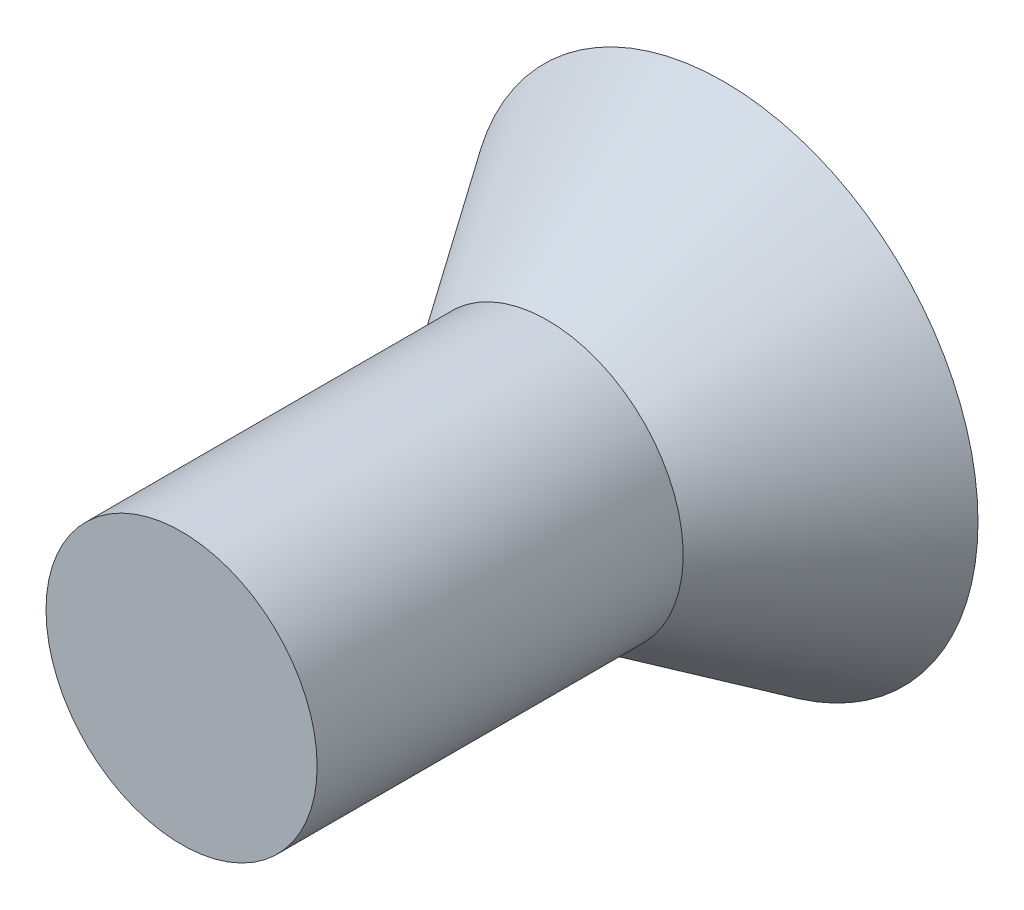
SolidWorks part; units mm, degrees
ref_plane "前视基准面" through (0, 0, 0) normal (0, 0, 1) x (1, 0, 0)
ref_plane "上视基准面" through (0, 0, 0) normal (0, 1, 0) x (1, 0, 0)
ref_plane "右视基准面" through (0, 0, 0) normal (1, 0, 0) x (0, 0, -1)
sketch "草图1" plane through (0, 0, 0) normal (0, 0, 1) x (1, 0, 0)
  circle A0 centre (0, 0) radius 2
extrude "凸台-拉伸1" add sketch "草图1" along normal blind 8
sketch "草图2" plane through (0, 0, 0) normal (0, 1, 0) x (1, 0, 0)
  line L0 (2, 0) -> (3.75, 0)
  line L1 (3.75, 0) -> (2, -2.6)
  line L2 (2, -8) -> (2, 0) construction
  line L3 (2, -2.6) -> (2, 0)
  line L4 (0, 0) -> (0, -2.9256) construction
revolve "旋转1" add sketch "草图2" angle 360 about L4
